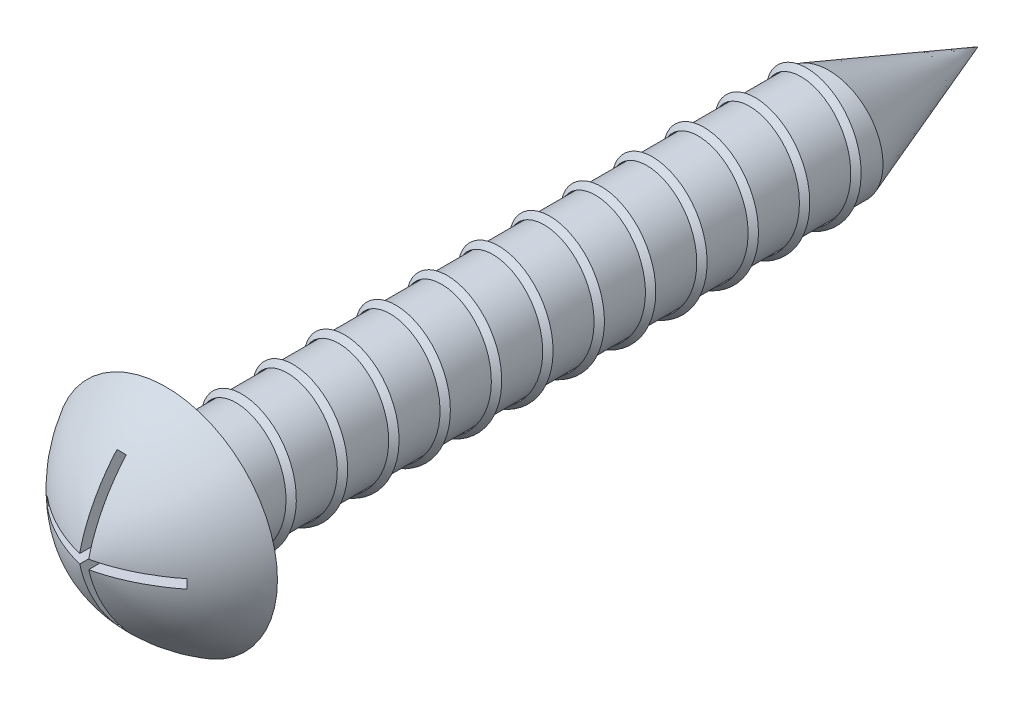
SolidWorks part; units mm, degrees
ref_plane "Front Plane" through (0, 0, 0) normal (0, 0, 1) x (1, 0, 0)
ref_plane "Top Plane" through (0, 0, 0) normal (0, 1, 0) x (1, 0, 0)
ref_plane "Right Plane" through (0, 0, 0) normal (1, 0, 0) x (0, 0, -1)
sketch "Sketch3" plane through (0, 0, 0) normal (1, 0, 0) x (0, 0, -1)
  line L0 (0, 0) -> (63.2524, 0)
  line L1 (63.2524, 0) -> (51.6195, 4.234)
  line L2 (51.6195, 4.234) -> (0, 4.234)
  line L3 (0, 4.234) -> (0, 8.6771)
  line L4 (0, 0) -> (-6.4111, 0)
  arc A0 (0, 8.6771) -> (-6.4111, 0) centre (6.5446, -2.8654) ccw
  point P8 (0, 0)
  dimension "D1" = 20
revolve "Revolve3" add sketch "Sketch3" angle 360 about L0
ref_plane "Plane1" through (0, 0, -51.6195) normal (0, 0, 1) x (1, 0, 0)
sketch "Sketch4" plane through (0, 0, -51.6195) normal (0, 0, 1) x (1, 0, 0)
  circle A0 centre (0, 0) radius 4.234 construction
  circle A1 centre (0, 0) radius 4.234
sketch "Sketch6" plane through (0, 0, -51.6195) normal (0, 0, 1) x (1, 0, 0)
  circle A0 centre (0, 0) radius 4.234 construction
  circle A1 centre (0, 0) radius 4.234
curve "Helix/Spiral2" pitch 4 height 48 turns 12
ref_plane "Plane2" through (-4.234, 0, -51.6195) normal (0, 0.9889, 0.1487) x (1, 0, 0)
sketch "Sketch7" plane through (-4.234, 0, -51.6195) normal (0, 0.9889, 0.1487) x (1, 0, 0)
  line L0 (0, 0) -> (-0.0649, -0.6185)
  line L1 (-0.0649, -0.6185) -> (-0.4255, -0.1735)
  line L2 (-0.4255, -0.1735) -> (0, 0)
sweep "Sweep1" add profiles "Sketch7" path "Helix/Spiral2"
sketch "Sketch9" plane through (0, 0, -51.6195) normal (0, 0, 1) x (1, 0, 0)
  circle A0 centre (0, 0) radius 4.234 construction
  circle A1 centre (0, 0) radius 4.234
curve "Helix/Spiral3" parameters "D10001"=7.5, "D30001"=4, "D40001"=3, "D10002"=0.5, "D30002"=3, "D40002"=3, "D50000"=3
sketch "Sketch10" plane through (0, -7.5899, -1.1412) normal (0, -0.9889, -0.1487) x (1, 0, 0)
  line L3 (-4.2989, -50.4272) -> (-4.6595, -50.8723)
  line L4 (-4.6595, -50.8723) -> (-4.234, -51.0458)
  line L5 (-4.234, -51.0458) -> (-4.2989, -50.4272)
  line L6 (-4.2989, -50.4272) -> (-4.6595, -50.8723)
  line L7 (-4.6595, -50.8723) -> (-4.234, -51.0458)
  line L8 (-4.234, -51.0458) -> (-4.2989, -50.4272)
  dimension "D1" = 0
ref_plane "Plane3" through (0, 0, 10) normal (0, 0, 1) x (1, 0, 0)
sketch "Sketch17" plane through (0, 0, 10) normal (0, 0, 1) x (1, 0, 0)
  line L0 (-6.7738, 0) -> (6.7738, 0) construction
  line L1 (-0.0822, 8.0065) -> (-0.0822, -8.0065) construction
  line L2 (-0.1038, 0.3522) -> (-0.0606, 0.3522)
  line L3 (-5.5881, 0.3522) -> (-0.4461, 0.3522)
  line L4 (-5.5881, 0.3522) -> (-5.5881, -0.3522)
  line L5 (-5.5881, -0.3522) -> (-0.4461, -0.3522)
  line L6 (5.4237, 0.3522) -> (5.4237, -0.3522)
  line L7 (-5.5881, 0.3522) -> (5.4237, -0.3522) construction
  line L8 (-5.5881, -0.3522) -> (5.4237, 0.3522) construction
  line L9 (-0.4461, 5.9285) -> (0.2818, 5.9285)
  line L10 (-0.4461, 5.9285) -> (-0.4461, 0.3522)
  line L11 (-0.4461, -5.9285) -> (0.2818, -5.9285)
  line L12 (0.2818, 5.9285) -> (0.2818, 0.3522)
  line L13 (-0.4461, 5.9285) -> (0.2818, -5.9285) construction
  line L14 (-0.4461, -5.9285) -> (0.2818, 5.9285) construction
  line L15 (-0.4461, 0.0233) -> (-0.4461, -0.0233)
  line L16 (-0.4461, -0.3522) -> (-0.4461, -5.9285)
  line L17 (-0.1038, -0.3522) -> (-0.0606, -0.3522)
  line L18 (0.2818, -0.3522) -> (5.4237, -0.3522)
  line L19 (0.2818, 0.3522) -> (5.4237, 0.3522)
  line L20 (0.2818, 0.0233) -> (0.2818, -0.0233)
  line L21 (0.2818, -0.3522) -> (0.2818, -5.9285)
  point P0 (-0.0822, 0)
  point P4 (0, 0)
  point P8 (-0.0822, 0)
  point P13 (-0.0822, 0)
extrude "Cut-Extrude1" cut sketch "Sketch17" against normal blind 10
